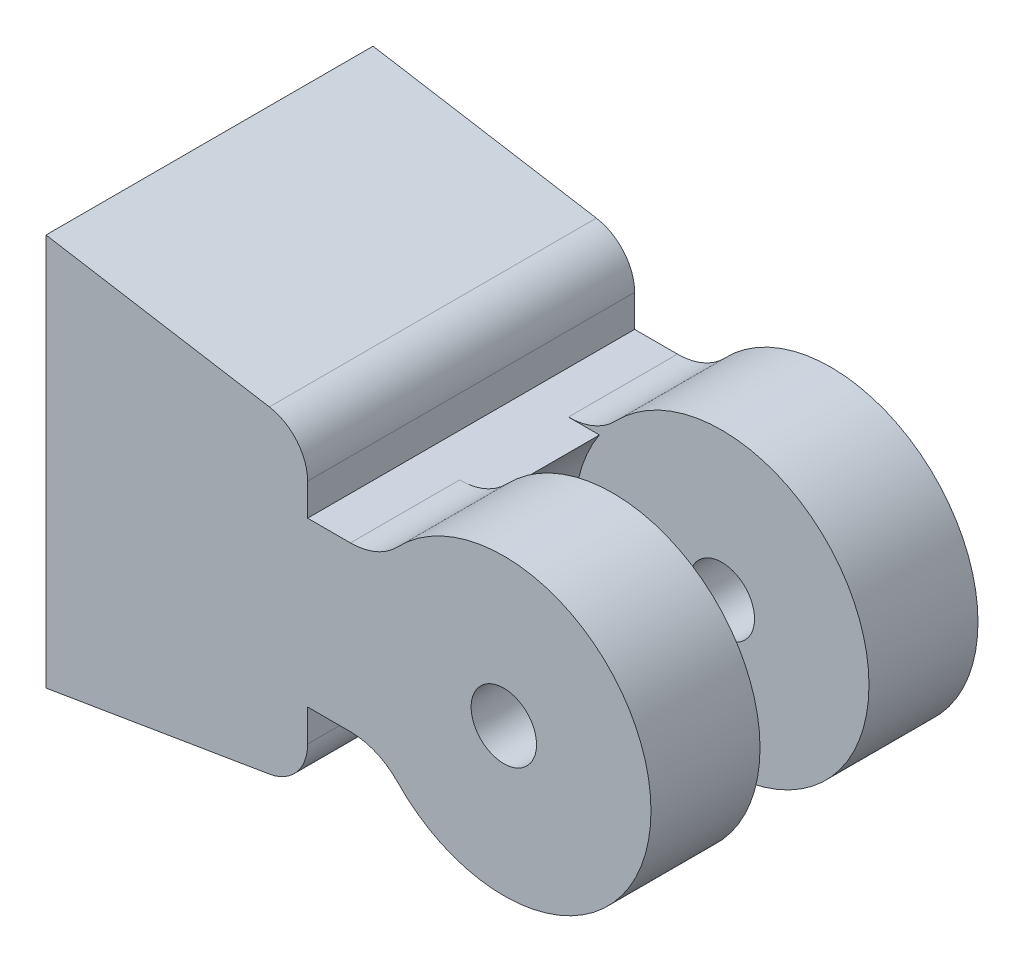
SolidWorks part; units mm, degrees
ref_plane "Front Plane" through (0, 0, 0) normal (0, 0, 1) x (1, 0, 0)
ref_plane "Top Plane" through (0, 0, 0) normal (0, 1, 0) x (1, 0, 0)
ref_plane "Right Plane" through (0, 0, 0) normal (1, 0, 0) x (0, 0, -1)
sketch "Sketch1" plane through (0, 0, 0) normal (0, 0, 1) x (1, 0, 0)
  line L0 (0, 30) -> (0, -30)
  line L1 (0, -30) -> (40, -23.335)
  line L2 (40, -23.335) -> (40, 23.335)
  line L3 (40, 23.335) -> (0, 30)
  line L4 (0, 30) -> (28.1182, 30) construction
  point P3 (40, 0)
  dimension "D1" = 9.46
  dimension "D2" = 40
  dimension "D3" = 60
extrude "Boss-Extrude1" add sketch "Sketch1" along normal blind 50
sketch "Sketch2" plane through (0, 0, 0) normal (0, 0, 1) x (1, 0, 0)
  line L0 (51.2917, -12.5) -> (40, -12.5)
  line L1 (51.2917, 12.5) -> (40, 12.5)
  line L2 (0, 30) -> (0, -30) construction
  line L3 (0, 0) -> (128.6531, 0) construction
  line L4 (40, -23.335) -> (40, 23.335) construction
  line L5 (40, 12.5) -> (40, -12.5)
  circle A0 centre (70, 0) radius 5
  circle A1 centre (70, 0) radius 22.5
  dimension "D1" = 70
  dimension "D2" = 25
  dimension "D3" = 10
  dimension "D4" = 45
extrude "Boss-Extrude2" add sketch "Sketch2" along normal blind 25 contours L5 L3 A1 L1 | L3 L5 L0 A1 | L3 A1 A0 | A1 L3 A0
sketch "Sketch3" plane through (0, 0, 25) normal (0, 0, 1) x (1, 0, 0)
  circle A0 centre (70, 0) radius 22.5
  arc A1 (51.2917, -12.5) -> (51.2917, 12.5) centre (70, 0) ccw construction
extrude "Cut-Extrude1" cut sketch "Sketch3" against normal blind 8.33
mirror "Mirror1" about plane through (0, 0, 25) normal (0, 0, 1) of "Cut-Extrude1", "Boss-Extrude2"
fillet "Fillet1" radius 10 4 edges at (51.2917, -12.5, 8.335) (51.2917, -12.5, 41.665) (51.2917, 12.5, 41.665) (51.2917, 12.5, 8.335)
fillet "Fillet2" radius 7 2 edges at (40, -23.335, 25) (40, 23.335, 25)
sketch "Sketch4" plane through (0, 0, 0) normal (-1, 0, 0) x (0, 0, 1)
  line L0 (50, 30) -> (0, 30) construction
  circle A0 centre (25, 0) radius 10
  point P5 (25, 30)
  dimension "D1" = 20
extrude "Cut-Extrude2" cut sketch "Sketch4" against normal blind 20
